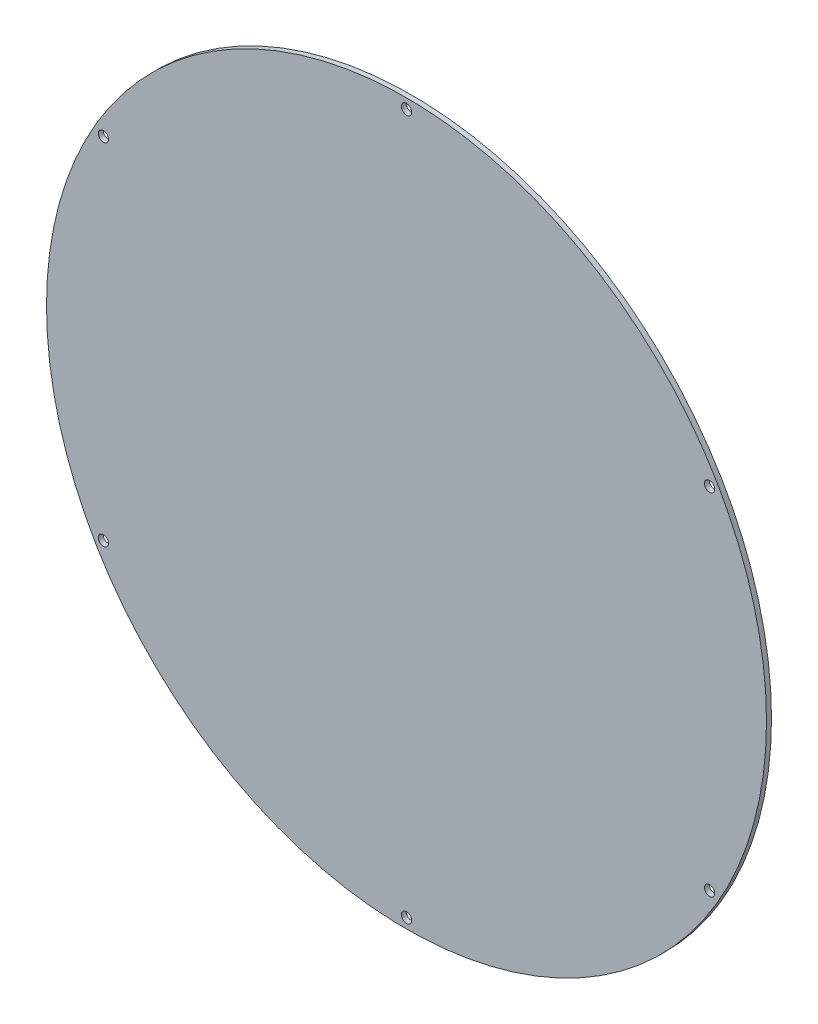
SolidWorks part; units mm, degrees
material "6061-T6 (SS)"
ref_plane "Front Plane" through (0, 0, 0) normal (0, 0, 1) x (1, 0, 0)
ref_plane "Top Plane" through (0, 0, 0) normal (0, 1, 0) x (1, 0, 0)
ref_plane "Right Plane" through (0, 0, 0) normal (1, 0, 0) x (0, 0, -1)
sketch "Sketch1" plane through (0, 0, 0) normal (0, 0, 1) x (1, 0, 0)
  circle A0 centre (0, 0) radius 114.3
  dimension "D1" = 228.6
extrude "Boss-Extrude1" add sketch "Sketch1" along normal blind 1.5875
sketch "Sketch2" plane through (0, 0, 1.5875) normal (0, 0, 1) x (1, 0, 0)
  circle A0 centre (0, 0) radius 111.125 construction
  circle A1 centre (0, 0) radius 114.3
  circle A2 centre (0, 0) radius 114.3
  point P1 (0, -111.125)
  point P5 (-96.2371, -55.5625)
  point P8 (-96.2371, 55.5625)
  point P9 (0, 111.125)
  point P10 (96.2371, 55.5625)
  point P11 (96.2371, -55.5625)
  dimension "D2" = 222.25
  dimension "D1" = 0
  dimension "D3" = 6
hole_wizard "#4 Clearance Hole1" positions "3DSketch1" profile "Sketch3" hole size "#4" standard "Ansi Inch" end condition through all
sketch3d "3DSketch1"
  point P0 (0, 111.125, 1.5875)
  point P3 (96.2371, 55.5625, 1.5875)
  point P6 (96.2371, -55.5625, 1.5875)
  point P9 (0, -111.125, 1.5875)
  point P12 (-96.2371, -55.5625, 1.5875)
  point P15 (-96.2371, 55.5625, 1.5875)
sketch "Sketch3" plane through (0, 111.125, 1.5875) normal (1, 0, 0) x (0, -1, 0)
  line L0 (0, 0) -> (0, 1.5875)
  line L1 (0, 1.5875) -> (1.6319, 1.5875)
  line L2 (1.6319, 1.5875) -> (1.6319, 0)
  line L5 (1.6319, 0) -> (0, 0)
  line L11 (0, -6.35) -> (0, 107.95) construction
  dimension "Thru Hole Dia." = 3.2639
  dimension "Thru Hole Depth" = 1.5875
